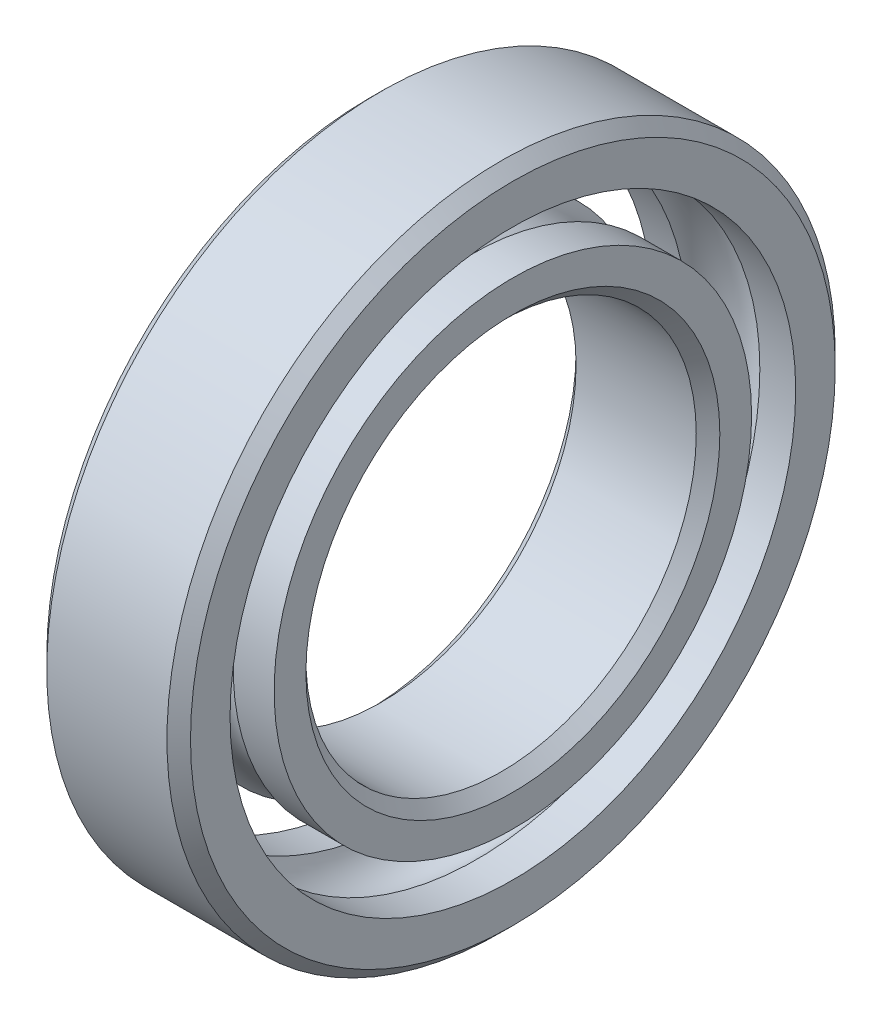
SolidWorks part; units mm, degrees
ref_plane "Спереди" through (0, 0, 0) normal (0, 0, 1) x (1, 0, 0)
ref_plane "Сверху" through (0, 0, 0) normal (0, 1, 0) x (1, 0, 0)
ref_plane "Справа" through (0, 0, 0) normal (1, 0, 0) x (0, 0, -1)
sketch "Эскиз1" plane through (0, 0, 0) normal (0, 0, 1) x (1, 0, 0)
  line L0 (1.7107, 19.1414) -> (-1.7107, 19.1414)
  line L1 (3.6877, 19.1414) -> (-3.6877, 19.1414) construction
  arc A0 (1.7107, 19.1414) -> (-1.7107, 19.1414) centre (0, 19.1414) ccw
  point P4 (0, 19.1414)
  point P7 (0, 19.1414)
  dimension "D1" = 3.4214
revolve "Повернуть1" add sketch "Эскиз1" angle 360 about L1
sketch "Эскиз3" plane through (0, 0, 0) normal (0, 0, 1) x (1, 0, 0)
  line L0 (3.0482, 19.9117) -> (1.5275, 19.9117)
  line L1 (2.5482, 16.1943) -> (-2.5482, 16.1943)
  line L2 (3.0482, 16.6943) -> (3.0482, 18.0418)
  line L3 (2.5482, 22.0886) -> (-2.5482, 22.0886)
  line L4 (-3.0482, 16.6943) -> (-3.0482, 18.0418)
  line L5 (3.0482, 16.1943) -> (-3.0482, 22.0886) construction
  line L6 (3.0482, 22.0886) -> (-3.0482, 16.1943) construction
  line L7 (3.0482, 18.0418) -> (1.3105, 18.0418)
  line L8 (3.0482, 19.9117) -> (3.0482, 21.5886)
  line L9 (-3.0482, 19.9117) -> (-3.0482, 21.5886)
  line L10 (-1.5275, 19.9117) -> (-3.0482, 19.9117)
  line L11 (-1.3105, 18.0418) -> (-3.0482, 18.0418)
  line L12 (3.0482, 21.5886) -> (2.5482, 22.0886)
  line L13 (-2.5482, 22.0886) -> (-3.0482, 21.5886)
  line L14 (-2.5482, 16.1943) -> (-3.0482, 16.6943)
  line L15 (3.0482, 16.6943) -> (2.5482, 16.1943)
  line L16 (7.7216, 0) -> (-7.7216, 0) construction
  line L17 (-7.7216, 7.9162) -> (7.7216, 7.9162) construction
  arc A0 (1.5275, 19.9117) -> (-1.5275, 19.9117) centre (0, 19.1414) ccw
  arc A1 (-1.3105, 18.0418) -> (1.3105, 18.0418) centre (0, 19.1414) ccw
  point P0 (0, 19.1414)
  point P26 (0, 0)
  dimension "D2" = 7.9162
surface "Поверхность-Повернуть1" sketch "Эскиз3" parameters "D1"=360
